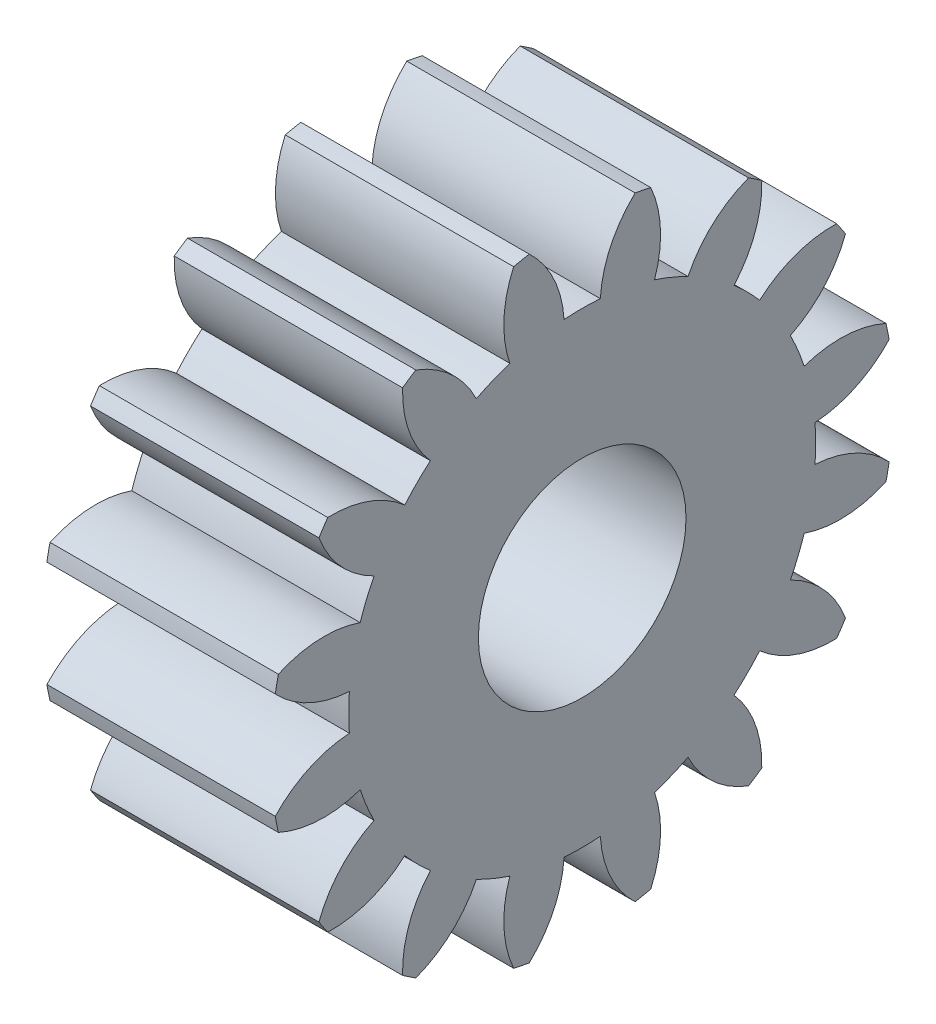
SolidWorks part; units mm, degrees
ref_plane "Plane1" through (0, 0, 0) normal (0, 0, 1) x (1, 0, 0)
ref_plane "Plane2" through (0, 0, 0) normal (0, 1, 0) x (1, 0, 0)
ref_plane "Plane3" through (0, 0, 0) normal (1, 0, 0) x (0, 0, -1)
sketch "HoldingSke" plane through (0, 0, 0) normal (0, 1, 0) x (1, 0, 0)
  line L0 (0, 0) -> (1.9225, -0.5513)
  line L1 (-15, 0) -> (100, 0) construction
  line L2 (0, 0) -> (-2.1039, 2.3779)
  line L3 (0, 0) -> (-11.863, 4.5341)
  line L4 (0, 0) -> (8.3015, 2.3804)
  line L5 (0, 0) -> (-46.8476, -17.4728)
  line L6 (0, 0) -> (-2.7356, -1.8457)
  line L7 (-2.1039, 2.3779) -> (8.6586, 51.2059)
  line L8 (-76.2, 54.61) -> (-75.7, 54.61)
  line L9 (-71.009, 38.7566) -> (-53.1078, 45.2721)
  line L10 (-76.2, 71.12) -> (104.1128, 71.12)
  line L11 (0, 0) -> (-3.3, 0)
  line L12 (-76.2, 101.6) -> (-76.181, 101.6)
  line L13 (24.9733, 27.94) -> (52.9518, 28.4284)
  line L14 (24.9733, 27.94) -> (24.9743, 27.94)
  line L15 (24.9733, 27.94) -> (100.4006, 29.5858)
  line L16 (-63.627, -0.5) -> (-12.827, -0.5)
  circle A0 centre (0, 0) radius 1.5
  circle A1 centre (0, 0) radius 3.374
  circle A2 centre (0, 0) radius 37.5
  circle A3 centre (0, 0) radius 1.5
  dimension "Hub_dia" = 75
  dimension "Bore" = 3
  dimension "MBD" = 3
  dimension "Overall_len" = 50
  dimension "Thickness" = 3.3
  dimension "OAL" = 50.0001
  dimension "T_dim" = 0.5
  dimension "Ap" = 20
  dimension "H" = 19.05
  dimension "Pitch_radius" = 180.3128
  dimension "Width" = 3.3
  dimension "Addendum_fac" = 1
  dimension "Dedendum_fac" = 1.25
  dimension "Clearance_fac" = 0.25
  dimension "Dedendum_add" = 0.001
sketch "BasProSke" plane through (0, 0, 0) normal (0, 1, 0) x (1, 0, 0)
  line L0 (-10, 0) -> (60, 0) construction
  line L1 (0, 0) -> (0, 4.5)
  line L2 (0, 0) -> (3.3, 0)
  line L3 (3.3, 0) -> (3.3, 4.5)
  line L4 (3.3, 4.5) -> (0, 4.5)
  dimension "Thickness" = 3.3
revolve "Base-Revolve" add sketch "BasProSke" angle 360 about L0
sketch "TooCutSke" plane through (0, 0, 0) normal (1, 0, 0) x (0, 0, -1)
  line L1 (0, 0) -> (0, 107) construction
  line L2 (0, 0) -> (-0.4253, 3.9773) construction
  line L3 (0, 0) -> (-1.5544, 7.8146) construction
  line L4 (-0.4253, 3.9773) -> (-0.7772, 3.9073) construction
  arc A0 (0.2619, 3.3638) -> (-0.2619, 3.3638) centre (0, 0) ccw
  arc A1 (0.7886, 4.4562) -> (-0.7886, 4.4562) centre (0, 0) ccw
  circle A2 centre (0, 0) radius 4 construction
  circle A3 centre (0, 0) radius 3.7588 construction
  arc A4 (-0.2619, 3.3638) -> (-0.7886, 4.4562) centre (-1.8589, 3.2669) ccw
  arc A5 (0.7886, 4.4562) -> (0.2619, 3.3638) centre (1.8589, 3.2669) ccw
extrude "ToothCut" cut sketch "TooCutSke" along normal through all
fillet "Breaks" [suppressed] radius 0.01
fillet "RootFillets" [suppressed] radius 0.126
pattern_circular "TeethCuts" count 16 every 22.5 about axis through (-10, 0, 0) along (1, 0, 0) of "ToothCut", "RootFillets", "Breaks"
sketch "HubNeaOneSke" plane through (0, 0, 0) normal (-1, 0, 0) x (0, 0, 1)
  circle A0 centre (0, 0) radius 3.374
extrude "HubNearOne" [suppressed] add sketch "HubNeaOneSke" along normal blind 46.7001
sketch "HubNeaBotSke" plane through (0, 0, 0) normal (-1, 0, 0) x (0, 0, 1)
  circle A0 centre (0, 0) radius 3.374
extrude "HubNearBoth" [suppressed] add sketch "HubNeaBotSke" along normal blind 23.35
ref_plane "FarPln" through (3.3, 0, 0) normal (1, 0, 0) x (0, 0, -1)
sketch "HubFarSke" plane through (3.3, 0, 0) normal (1, 0, 0) x (0, 0, -1)
  circle A0 centre (0, 0) radius 3.374
extrude "HubFar" [suppressed] add sketch "HubFarSke" along normal blind 23.35
sketch "BorSke" plane through (0, 0, 0) normal (1, 0, 0) x (0, 0, -1)
  circle A0 centre (0, 0) radius 1.5
  dimension "Diameter" = 3
extrude "Bore" cut sketch "BorSke" along normal mid plane 100.0001
sketch "KeySke" plane through (0, 0, 0) normal (1, 0, 0) x (0, 0, -1)
  line L0 (-0.6, 0) -> (-0.6, 2)
  line L1 (-0.6, 2) -> (0.6, 2)
  line L2 (0.6, 2) -> (0.6, 0)
  line L3 (0, 0) -> (0, 34) construction
  line L4 (-0.6, 0) -> (0.6, 0)
  dimension "Offset" = 2
  dimension "Width" = 1.2
extrude "Keyway" [suppressed] cut sketch "KeySke" along normal mid plane 100.0001
pattern_circular "Keyway2" [suppressed] count 2 every 90 about axis through (-10, 0, 0) along (1, 0, 0)
equation "' \"Module@HoldingSke\" = 6.35"
equation "' \"Num_teeth@HoldingSke\" = 12"
equation "' \"Ap@HoldingSke\" =  20"
equation "' \"Ap@HoldingSke\" = 20"
equation "' \"Width@HoldingSke\" = 0.5 * 25.4"
equation "' \"Hub_dia@HoldingSke\"= 1 * 25.4"
equation "' \"Hub_dia@HoldingSke\" = 1 * 25.4"
equation "' \"Overall_len@HoldingSke\" = 1.0 * 25.4"
equation "' \"Bore@HoldingSke\" = 0.75 * 25.4"
equation "' \"T_dim@HoldingSke\" = 0.1 * 25.4"
equation "' \"Width@KeySke\" = 0.25 * 25.4"
equation "' \"Show_teeth@HoldingSke\" = 13"
equation "' \"Backlash@HoldingSke\" = 0.009 * 25.4"
equation "' \"Addendum_fac@HoldingSke\" = 1.0"
equation "' \"Dedendum_fac@HoldingSke\" = 1.25"
equation "' \"Dedendum_add@HoldingSke\" = 0.00005 * 25.4"
equation "' \"Clearance_fac@HoldingSke\" = 0.25"
equation "\"Pitch@HoldingSke\" = 1 / \"Module@HoldingSke\""
equation "\"Overcut_dia@TooCutSke\" = (\"Num_teeth@HoldingSke\" + 2 * \"Addendum_fac@HoldingSke\") / \"Pitch@HoldingSke\" + 0.002 * 25.4"
equation "\"Pitch_dia@TooCutSke\" = \"Num_teeth@HoldingSke\" / \"Pitch@HoldingSke\""
equation "\"Base_dia@TooCutSke\" = \"Num_teeth@HoldingSke\" / \"Pitch@HoldingSke\" * cos((\"Ap@HoldingSke\"  * 3.14159265 / 180))"
equation "\"Root_dia@TooCutSke\" = (\"Num_teeth@HoldingSke\" + 2) / \"Pitch@HoldingSke\" - 2 * (\"Addendum_fac@HoldingSke\" + \"Dedendum_fac@HoldingSke\") / \"Pitch@HoldingSke\" - \"Dedendum_add@HoldingSke\" * 2"
equation "\"Half_ang@TooCutSke\" = 180 / \"Num_teeth@HoldingSke\""
equation "\"Half_CT@TooCutSke\" = \"Num_teeth@HoldingSke\" / \"Pitch@HoldingSke\" * sin((3.14159265 / 2 / \"Num_teeth@HoldingSke\")) / 2 - 7 * \"Backlash@HoldingSke\" / 4"
equation "\"Flank_rad@TooCutSke\" = \"Num_teeth@HoldingSke\" / \"Pitch@HoldingSke\" / 5"
equation "\"Radius@RootFillets\" = \"Clearance_fac@HoldingSke\" / \"Pitch@HoldingSke\" + \"Dedendum_add@HoldingSke\""
equation "\"Break_rad@Breaks\" = 0.02 / \"Pitch@HoldingSke\""
equation "\"Thickness@HoldingSke\" = \"Width@HoldingSke\""
equation "\"OAL@HoldingSke\" = \"Thickness@HoldingSke\""
equation "\"MHD@HoldingSke\" = (\"Num_teeth@HoldingSke\" + 2) / \"Pitch@HoldingSke\" - 2 * (\"Addendum_fac@HoldingSke\" + \"Dedendum_fac@HoldingSke\")  / \"Pitch@HoldingSke\" - \"Dedendum_add@HoldingSke\" * 2"
equation "\"MBD@HoldingSke\" = (\"Num_teeth@HoldingSke\" + 2) / \"Pitch@HoldingSke\" - 2 * (\"Addendum_fac@HoldingSke\" + \"Dedendum_fac@HoldingSke\")  / \"Pitch@HoldingSke\" - \"Dedendum_add@HoldingSke\" * 2 - 0.002 * 25.4"
equation "\"MHD@HoldingSke\" = ((sgn( \"MHD@HoldingSke\" - \"Hub_dia@HoldingSke\" )-1)*( \"MHD@HoldingSke\" - \"Hub_dia@HoldingSke\" ))/-2+ \"Hub_dia@HoldingSke\""
equation "\"MBD@HoldingSke\" = ((sgn( \"MBD@HoldingSke\" - \"Bore@HoldingSke\" )-1)*( \"MBD@HoldingSke\" - \"Bore@HoldingSke\" ))/-2+ \"Bore@HoldingSke\""
equation "\"OAL@HoldingSke\" = ((sgn( \"OAL@HoldingSke\" - \"Overall_len@HoldingSke\" )+1)*( \"OAL@HoldingSke\" - \"Overall_len@HoldingSke\" ))/2 + \"Overall_len@HoldingSke\" + 0.000002 * 25.4"
equation "\"Num_teeth@TeethCuts\" = int( \"Show_teeth@HoldingSke\" ) + 1"
equation "\"Num_teeth@TeethCuts\" = ((sgn( \"Num_teeth@TeethCuts\" - \"Num_teeth@HoldingSke\" )-1)*( \"Num_teeth@TeethCuts\" - \"Num_teeth@HoldingSke\" ))/-2+ \"Num_teeth@HoldingSke\""
equation "\"Num_teeth@TeethCuts\" = ((sgn( \"Num_teeth@TeethCuts\" - 2.0)+1)*( \"Num_teeth@TeethCuts\" - 2.0))/2 +2.0"
equation "\"Angle@TeethCuts\" = 360.0 / \"Num_teeth@HoldingSke\""
equation "\"Diameter@BasProSke\" = (\"Num_teeth@HoldingSke\" + 2 * \"Addendum_fac@HoldingSke\") / \"Pitch@HoldingSke\""
equation "\"Thickness@BasProSke\"  = \"Thickness@HoldingSke\""
equation "' \"Fillet_rad@BasProSke\" =  \"Thickness@HoldingSke\" * 0.05"
equation "' \"Fillet_rad@BasProSke\" = \"Thickness@HoldingSke\" * 0.05"
equation "\"MHD@HoldingSke\" = ((sgn( \"MHD@HoldingSke\" - \"Root_dia@TooCutSke\" )-1)*( \"MHD@HoldingSke\" - \"Root_dia@TooCutSke\" ))/-2+ \"Root_dia@TooCutSke\""
equation "\"Diameter@HubNeaOneSke\" = \"MHD@HoldingSke\""
equation "\"Length@HubNearOne\" = \"OAL@HoldingSke\" - \"Thickness@BasProSke\""
equation "\"Diameter@HubNeaBotSke\" = \"MHD@HoldingSke\""
equation "\"Length@HubNearBoth\" = ( \"OAL@HoldingSke\" - \"Thickness@BasProSke\" ) / 2.0"
equation "\"Thickness@FarPln\" = \"Thickness@BasProSke\""
equation "\"Diameter@HubFarSke\" = \"MHD@HoldingSke\""
equation "\"Length@HubFar\" = ( \"OAL@HoldingSke\" - \"Thickness@BasProSke\" ) / 2.0"
equation "\"Diameter@BorSke\" = \"MBD@HoldingSke\""
equation "\"D1@Bore\" = \"OAL@HoldingSke\" * 2.0"
equation "\"D1@Keyway\" = \"OAL@HoldingSke\" * 2.0"
equation "\"Offset@KeySke\" = \"T_dim@HoldingSke\" + \"MBD@HoldingSke\" / 2.0"
